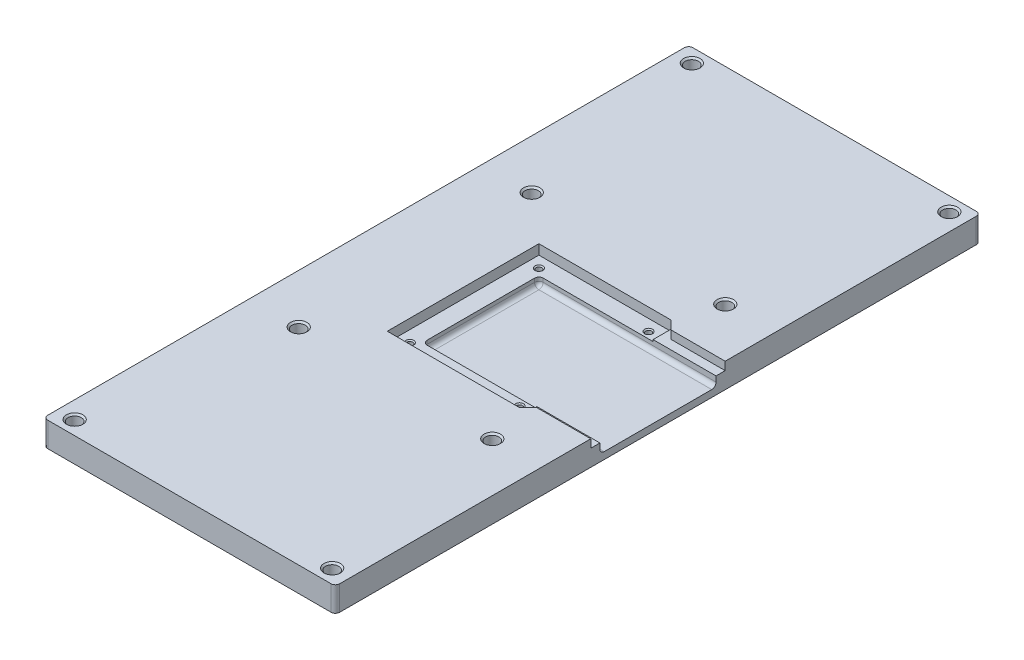
SolidWorks part; units mm, degrees
ref_plane "Front Plane" through (0, 0, 0) normal (0, 0, 1) x (1, 0, 0)
ref_plane "Top Plane" through (0, 0, 0) normal (0, 1, 0) x (1, 0, 0)
ref_plane "Right Plane" through (0, 0, 0) normal (1, 0, 0) x (0, 0, -1)
sketch "Sketch1" plane through (0, 0, 0) normal (0, 1, 0) x (1, 0, 0)
  line L0 (0, -135) -> (0, 135) construction
  line L1 (67.875, 135) -> (-67.875, 135) construction
  line L2 (-67.875, 135) -> (-67.875, -135)
  line L3 (-67.875, 0) -> (67.875, 0) construction
  line L4 (-67.875, 135) -> (-67.875, 148)
  line L5 (-65.875, 150) -> (65.875, 150)
  line L6 (0, 150) -> (0, 135) construction
  line L7 (67.875, 135) -> (67.875, 148)
  line L8 (67.875, 135) -> (67.875, -135)
  line L9 (0, -150) -> (0, -135) construction
  line L10 (67.875, -135) -> (-67.875, -135) construction
  line L11 (67.875, -135) -> (67.875, -148)
  line L12 (-65.875, -150) -> (65.875, -150)
  line L13 (-67.875, -135) -> (-67.875, -148)
  line L14 (-67.875, 138) -> (67.875, 138) construction
  circle A1 centre (-59.875, 143.5) radius 3.075 construction
  circle A2 centre (59.875, 143.5) radius 3.075 construction
  circle A5 centre (59.875, -143.5) radius 3.075 construction
  circle A6 centre (-59.875, -143.5) radius 3.075 construction
  arc A8 (-65.875, -150) -> (-67.875, -148) centre (-65.875, -148) cw
  arc A9 (67.875, -148) -> (65.875, -150) centre (65.875, -148) cw
  arc A10 (67.875, 148) -> (65.875, 150) centre (65.875, 148) ccw
  arc A11 (-67.875, 148) -> (-65.875, 150) centre (-65.875, 148) cw
  circle A12 centre (-45, 54.175) radius 3.075 construction
  circle A13 centre (45, 54.175) radius 3.075 construction
  circle A14 centre (45, -54.175) radius 3.075 construction
  circle A15 centre (-45, -54.175) radius 3.075 construction
  point P24 (0, 0)
  point P36 (-67.875, -150)
  point P39 (67.875, -150)
  point P42 (67.875, 150)
  point P45 (-67.875, 150)
  dimension "D5" = 54.175
  dimension "D10" = 2
  dimension "D3" = 6.15
  dimension "D1" = 67.875
  dimension "D2" = 135
  dimension "D4" = 6.5
  dimension "D6" = 8
  dimension "D7" = 8.5
  dimension "D8" = 12
  dimension "D9" = 3
  dimension "D11" = 150
  dimension "D12" = 45
extrude "Boss-Extrude1" add sketch "Sketch1" along normal blind 11.5
sketch "Sketch3" plane through (0, 11.5, 0) normal (0, 1, 0) x (1, 0, 0)
  line L0 (0, 0) -> (-67.875, 0) construction
  line L1 (-67.875, 148) -> (-67.875, -148) construction
  line L2 (0, 0) -> (0, 150) construction
  line L3 (65.875, 150) -> (-65.875, 150) construction
  line L4 (3.96, -16.3) -> (3.96, 16.3)
  line L5 (-2.46, -17.8) -> (2.46, -17.8)
  line L6 (-3.96, 16.3) -> (-3.96, -16.3)
  line L7 (2.46, 17.8) -> (-2.46, 17.8)
  line L8 (0, 17.8) -> (0, -17.8) construction
  line L9 (13.25, 0) -> (0, 0) construction
  line L10 (16.15, 10.025) -> (10.35, 10.025)
  line L11 (16.15, 10.025) -> (16.15, -10.025)
  line L12 (16.15, -10.025) -> (10.35, -10.025)
  line L13 (10.35, 10.025) -> (10.35, -10.025)
  line L14 (16.15, 10.025) -> (10.35, -10.025) construction
  line L15 (16.15, -10.025) -> (10.35, 10.025) construction
  line L16 (13.25, 0) -> (13.25, 10.025) construction
  line L17 (-16.15, 10.025) -> (-16.15, -10.025)
  line L18 (-16.15, -10.025) -> (-10.35, -10.025)
  line L23 (-16.15, 10.025) -> (-10.35, 10.025)
  line L24 (-10.35, 10.025) -> (-10.35, -10.025)
  arc A0 (-2.46, 17.8) -> (-3.96, 16.3) centre (-2.46, 16.3) ccw
  arc A1 (3.96, 16.3) -> (2.46, 17.8) centre (2.46, 16.3) ccw
  arc A2 (2.46, -17.8) -> (3.96, -16.3) centre (2.46, -16.3) ccw
  arc A3 (-3.96, -16.3) -> (-2.46, -17.8) centre (-2.46, -16.3) ccw
  point P9 (0, 0)
  point P23 (0, 0)
  dimension "D2" = 1.5
  dimension "D1" = 35.6
  dimension "D3" = 7.92
  dimension "D4" = 20.05
  dimension "D5" = 5.8
  dimension "D6" = 13.25
sketch "Sketch4" plane through (0, 11.5, 0) normal (0, 1, 0) x (1, 0, 0)
  circle A0 centre (-59.875, -143.5) radius 3.075 construction
  circle A1 centre (59.875, -143.5) radius 3.075 construction
  circle A2 centre (59.875, 143.5) radius 3.075 construction
  circle A3 centre (45, -54.175) radius 3.075 construction
  circle A4 centre (-45, -54.175) radius 3.075 construction
  circle A5 centre (-59.875, 143.5) radius 3.075 construction
  circle A6 centre (45, 54.175) radius 3.075 construction
  circle A7 centre (-45, 54.175) radius 3.075 construction
  circle A8 centre (-59.875, -143.5) radius 3.075
  circle A9 centre (59.875, -143.5) radius 3.075
  circle A10 centre (59.875, 143.5) radius 3.075
  circle A13 centre (-59.875, 143.5) radius 3.075
  circle A14 centre (45, -54.175) radius 3.075
  circle A15 centre (-45, -54.175) radius 3.075
  circle A16 centre (45, 54.175) radius 3.075
  circle A17 centre (-45, 54.175) radius 3.075
extrude "Cut-Extrude1" cut sketch "Sketch4" against normal blind 6
sketch "Sketch21" plane through (0, 11.5, 0) normal (0, 1, 0) x (1, 0, 0)
  line L0 (38.5, 35) -> (-22.5, 35) construction
  line L1 (38.5, 35) -> (42.5, 31) construction
  line L2 (-22.5, 35) -> (-22.5, -35) construction
  line L3 (-22.5, 0) -> (0, 0) construction
  line L4 (0, 0) -> (38.5, 0) construction
  line L5 (38.5, -35) -> (38.5, 35) construction
  line L6 (38.5, -35) -> (-22.5, -35) construction
  line L7 (42.5, 31) -> (67.875, 31) construction
  line L8 (67.875, -148) -> (67.875, 148) construction
  line L9 (67.875, 31) -> (67.875, -31)
  line L10 (67.875, 0) -> (38.5, 0) construction
  line L11 (42.5, -31) -> (67.875, -31) construction
  line L12 (38.5, -35) -> (42.5, -31) construction
  line L13 (42.6036, 31.25) -> (67.875, 31.25)
  line L14 (38.6036, 35.25) -> (42.6036, 31.25)
  line L15 (38.6036, 35.25) -> (-22.75, 35.25)
  line L16 (-22.75, 35.25) -> (-22.75, -35.25)
  line L17 (38.6036, -35.25) -> (-22.75, -35.25)
  line L18 (38.6036, -35.25) -> (42.6036, -31.25)
  line L19 (42.6036, -31.25) -> (67.875, -31.25)
  line L20 (67.875, -31.25) -> (67.875, -31)
  line L21 (67.875, 31) -> (67.875, 31.25)
  circle A0 centre (-17.5, 30) radius 1.6 construction
  circle A1 centre (33.5, 30) radius 1.6 construction
  circle A2 centre (33.5, -30) radius 1.6 construction
  circle A3 centre (-17.5, -30) radius 1.6 construction
  dimension "D8" = 3.2
  dimension "D1" = 22.5
  dimension "D2" = 61
  dimension "D3" = 35
  dimension "D4" = 5
  dimension "D5" = 5
  dimension "D6" = 5
  dimension "D7" = 5
  dimension "D9" = 45
  dimension "D10" = 4
  dimension "D12" = 25.375
  dimension "D11" = 0.25
extrude "Cut-Extrude6" cut sketch "Sketch21" against normal blind 4.6
sketch "Sketch24" plane through (0, 6.9, 0) normal (0, 1, 0) x (1, 0, 0)
  line L0 (67.875, 27) -> (-14.5, 27)
  line L2 (-14.5, 27) -> (-14.5, -27)
  line L3 (-14.5, -27) -> (67.875, -27)
  line L4 (67.875, -27) -> (67.875, 27)
  line L8 (38.5, 35) -> (-22.5, 35) construction
  line L10 (-22.5, 35) -> (-22.5, -35) construction
  line L11 (38.5, -35) -> (-22.5, -35) construction
  line L12 (67.875, -31.25) -> (67.875, 31.25) construction
  dimension "D1" = 8
  dimension "D2" = 8
  dimension "D3" = 8
extrude "Cut-Extrude3" cut sketch "Sketch24" against normal blind 3.7 and the other way through all
sketch "Sketch25" plane through (0, 6.9, 0) normal (0, 1, 0) x (1, 0, 0)
  circle A0 centre (33.5, 30) radius 1.35
  circle A1 centre (-17.5, 30) radius 1.35
  circle A2 centre (33.5, -30) radius 1.35
  circle A3 centre (-17.5, -30) radius 1.35
  dimension "D1" = 2.7
extrude "Cut-Extrude4" cut sketch "Sketch25" against normal blind 5
chamfer "Chamfer4" distance 0.5 angle 45 4 edges at (-17.5, 6.9, 31.35) (33.5, 6.9, 31.35) (33.5, 6.9, -28.65) (-17.5, 6.9, -28.65)
fillet "Fillet1" radius 2 5 edges at (26.6875, 3.2, 27) (-14.5, 5.05, 27) (-14.5, 5.05, -27) (-14.5, 3.2, 0) (26.6875, 3.2, -27)
sketch "Sketch26" plane through (0, 6.9, 0) normal (0, 1, 0) x (1, 0, 0)
  line L0 (0, 0) -> (67.875, 0) construction
  line L1 (67.875, -25) -> (67.875, 25) construction
  line L2 (38.6036, 35.25) -> (38.6036, 27)
  line L3 (67.875, 27) -> (-12.5, 27) construction
  line L4 (38.6036, 27) -> (67.875, 27)
  line L5 (67.875, 27) -> (67.875, 31.25)
  line L6 (67.875, 31.25) -> (42.6036, 31.25)
  line L7 (42.6036, 31.25) -> (38.6036, 35.25)
  line L8 (42.6036, -31.25) -> (38.6036, -35.25)
  line L9 (67.875, -31.25) -> (42.6036, -31.25)
  line L10 (67.875, -27) -> (67.875, -31.25)
  line L11 (38.6036, -27) -> (67.875, -27)
  line L12 (38.6036, -35.25) -> (38.6036, -27)
extrude "Boss-Extrude2" add sketch "Sketch26" along normal blind 0.8
chamfer "Chamfer5" distance 0.75 angle 45 8 edges at (59.875, 11.5, 146.575) (-59.875, 11.5, 146.575) (-59.875, 11.5, -140.425) (59.875, 11.5, -140.425) (-45, 11.5, 57.25) (45, 11.5, 57.25) (45, 11.5, -51.1) (-45, 11.5, -51.1)
equation "\"D5@Sketch21\"=\"D4@Sketch21\""
equation "\"D6@Sketch21\"=\"D4@Sketch21\""
equation "\"D7@Sketch21\"=\"D4@Sketch21\""
equation "\"D2@Sketch24\"=\"D1@Sketch24\""
equation "\"D3@Sketch24\"=\"D1@Sketch24\""
